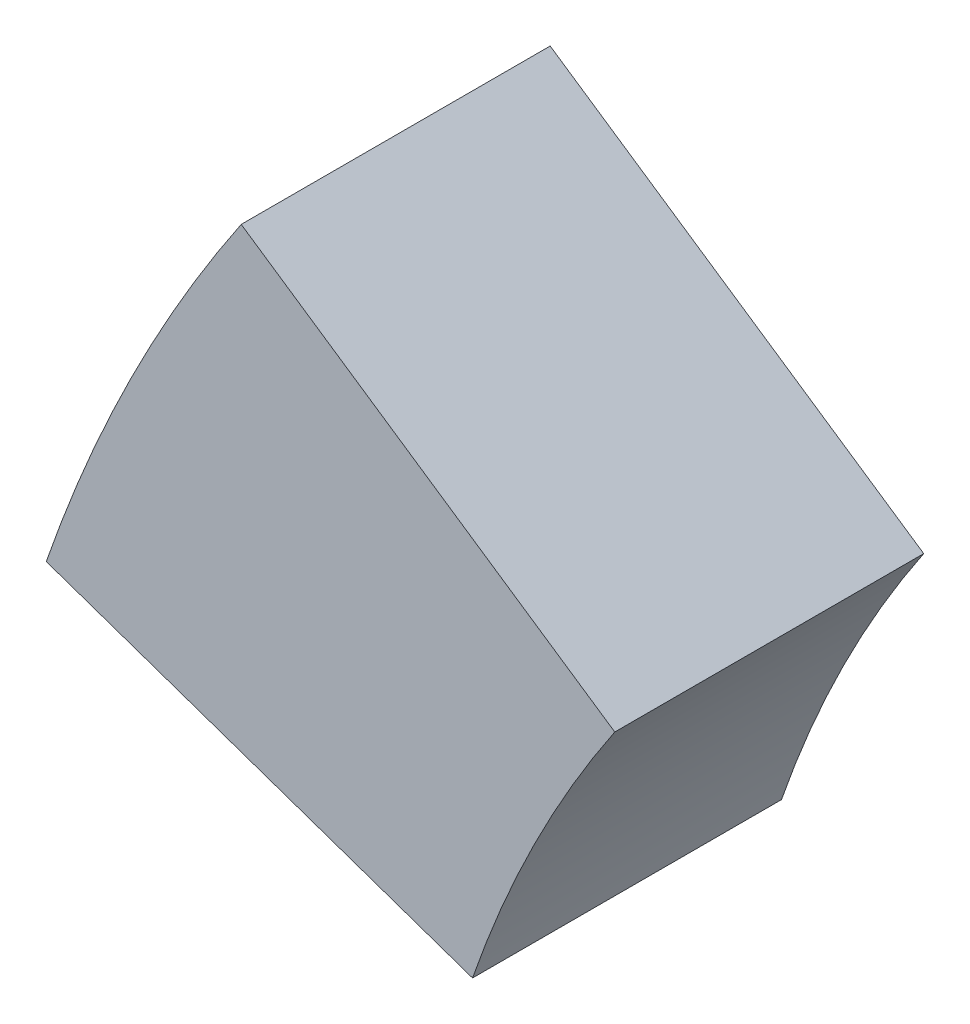
SolidWorks part; units mm, degrees
ref_plane "Plano frontal" through (0, 0, 0) normal (0, 0, 1) x (1, 0, 0)
ref_plane "Plano superior" through (0, 0, 0) normal (0, 1, 0) x (1, 0, 0)
ref_plane "Plano direito" through (0, 0, 0) normal (1, 0, 0) x (0, 0, -1)
sketch "Esboço1" plane through (0, 0, 0) normal (0, 0, 1) x (1, 0, 0)
  line L2 (-223.6039, 151.3318) -> (-163.148, 110.4161)
  line L3 (-255.1523, 88.3023) -> (-186.1667, 64.428)
  arc A0 (-186.1667, 64.428) -> (-163.148, 110.4161) centre (0, 0) cw
  arc A1 (-255.1523, 88.3023) -> (-223.6039, 151.3318) centre (0, 0) cw
  dimension "D2" = 197
  dimension "D3" = 270
  dimension "D1" = 15
extrude "Ressalto-extrusão1" add sketch "Esboço1" along normal blind 50
